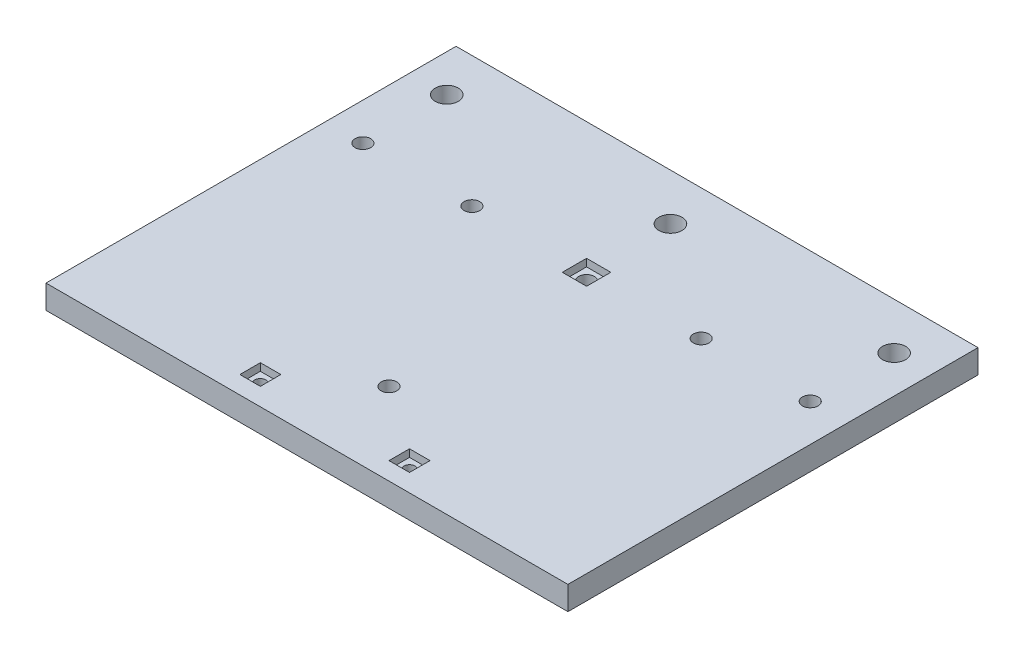
SolidWorks part; units mm, degrees
ref_plane "Front Plane" through (0, 0, 0) normal (0, 0, 1) x (1, 0, 0)
ref_plane "Top Plane" through (0, 0, 0) normal (0, 1, 0) x (1, 0, 0)
ref_plane "Right Plane" through (0, 0, 0) normal (1, 0, 0) x (0, 0, -1)
sketch "Sketch2" plane through (0, 0, 0) normal (0, 1, 0) x (1, 0, 0)
  line L0 (0, 85) -> (140, 85) construction
  line L1 (0, 0) -> (140, 0)
  line L2 (0, 0) -> (0, 110)
  line L3 (0, 110) -> (140, 110)
  line L4 (140, 0) -> (140, 110)
  line L5 (0, 97.5) -> (140, 97.5) construction
  line L6 (0, 7.5) -> (140, 7.5) construction
  line L7 (67, 78) -> (73, 78)
  line L8 (67, 78) -> (67, 72)
  line L9 (67, 72) -> (73, 72)
  line L10 (73, 78) -> (73, 72)
  line L11 (67, 78) -> (73, 72) construction
  line L12 (67, 72) -> (73, 78) construction
  circle A0 centre (39.25, 75) radius 2.1
  circle A1 centre (100.75, 75) radius 2.1
  circle A2 centre (70, 22) radius 2.1
  circle A3 centre (10, 97.5) radius 3.1
  circle A4 centre (70, 97.5) radius 3.1
  circle A5 centre (130, 97.5) radius 3.1
  circle A6 centre (10, 75) radius 2.1
  circle A7 centre (70, 75) radius 2.1
  circle A8 centre (130, 75) radius 2.1
  circle A9 centre (50, 7.5) radius 1.5
  circle A10 centre (90, 7.5) radius 1.5
  point P35 (0, 0)
  dimension "D1" = 4.2
  dimension "D11" = 6.2
  dimension "D15" = 4.2
  dimension "D23" = 3
  dimension "D2" = 61.5
  dimension "D3" = 140
  dimension "D4" = 110
  dimension "D5" = 30.75
  dimension "D6" = 53
  dimension "D7" = 70
  dimension "D8" = 35
  dimension "D9" = 25
  dimension "D10" = 12.5
  dimension "D12" = 10
  dimension "D14" = 60
  dimension "D16" = 10
  dimension "D17" = 10
  dimension "D19" = 60
  dimension "D20" = 6
  dimension "D21" = 6
  dimension "D22" = 7.5
  dimension "D25" = 50
  dimension "D26" = 40
  dimension "D13" = 3
  dimension "D18" = 3
  dimension "D24" = 2
extrude "Boss-Extrude2" add sketch "Sketch2" along normal blind 6.35 contours L1 L4 L3 L2 A8 A6 A5 A4 A3 A2 A1 A0 L7 L10 L9 L8 | L10 L7 L8 L9 A7
sketch "Sketch3" plane through (0, 6.35, 0) normal (0, 1, 0) x (1, 0, 0)
  line L1 (66.75, 71.75) -> (73.25, 71.75)
  line L2 (66.75, 71.75) -> (66.75, 78.25)
  line L3 (66.75, 78.25) -> (73.25, 78.25)
  line L4 (73.25, 71.75) -> (73.25, 78.25)
  line L5 (66.75, 71.75) -> (73.25, 78.25) construction
  line L6 (66.75, 78.25) -> (73.25, 71.75) construction
  line L7 (47.25, 4.75) -> (52.75, 4.75)
  line L8 (47.25, 4.75) -> (47.25, 10.25)
  line L9 (47.25, 10.25) -> (52.75, 10.25)
  line L10 (52.75, 4.75) -> (52.75, 10.25)
  line L11 (47.25, 4.75) -> (52.75, 10.25) construction
  line L12 (47.25, 10.25) -> (52.75, 4.75) construction
  line L13 (87.25, 4.75) -> (92.75, 4.75)
  line L14 (87.25, 4.75) -> (87.25, 10.25)
  line L15 (87.25, 10.25) -> (92.75, 10.25)
  line L16 (92.75, 4.75) -> (92.75, 10.25)
  line L17 (87.25, 4.75) -> (92.75, 10.25) construction
  line L18 (87.25, 10.25) -> (92.75, 4.75) construction
  point P0 (70, 75)
  point P6 (50, 7.5)
  point P12 (90, 7.5)
  dimension "D1" = 6.5
  dimension "D2" = 6.5
  dimension "D3" = 5.5
  dimension "D4" = 5.5
  dimension "D5" = 5.5
  dimension "D6" = 5.5
extrude "Cut-Extrude1" cut sketch "Sketch3" against normal blind 2
equation "\"D10@Sketch2\"=25/2"
